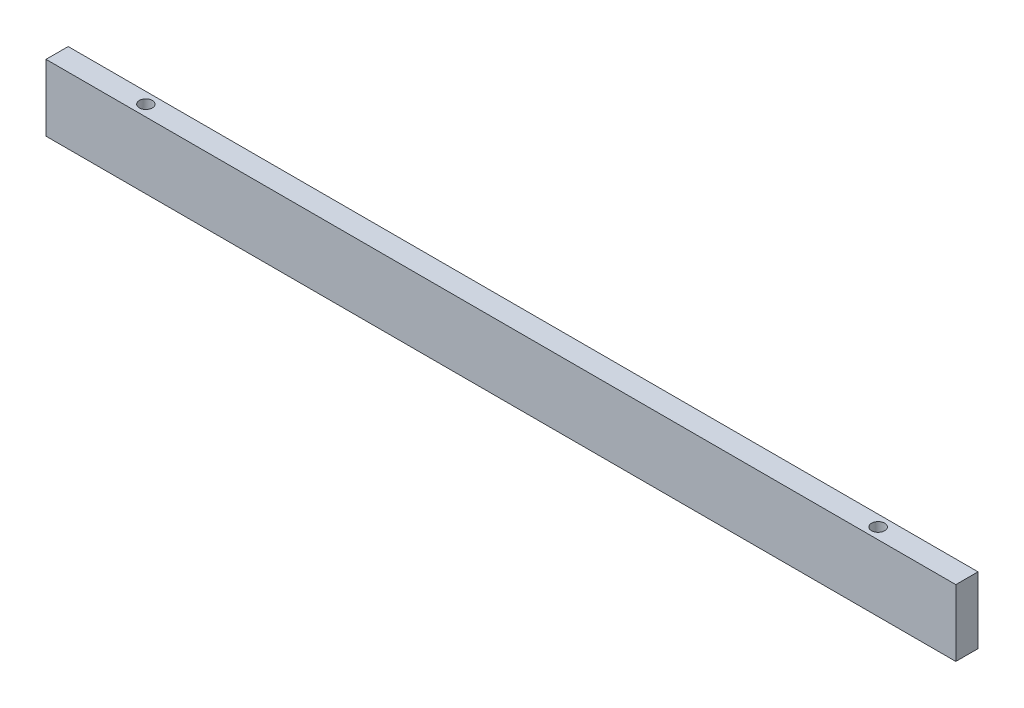
SolidWorks part; units mm, degrees
ref_plane "Front Plane" through (0, 0, 0) normal (0, 0, 1) x (1, 0, 0)
ref_plane "Top Plane" through (0, 0, 0) normal (0, 1, 0) x (1, 0, 0)
ref_plane "Right Plane" through (0, 0, 0) normal (1, 0, 0) x (0, 0, -1)
sketch "Sketch1" plane through (0, 0, 0) normal (0, 0, 1) x (1, 0, 0)
  line L0 (0, 0) -> (260.35, 0)
  line L1 (260.35, 0) -> (260.35, -19.05)
  line L2 (260.35, -19.05) -> (0, -19.05)
  line L3 (0, -19.05) -> (0, 0)
extrude "Boss-Extrude1" add sketch "Sketch1" along normal blind 6.35
sketch "Sketch2" plane through (0, 0, 0) normal (0, 1, 0) x (1, 0, 0)
  line L0 (260.35, -6.35) -> (260.35, 0) construction
  line L1 (0, -6.35) -> (0, 0) construction
  circle A0 centre (234.95, -3.175) radius 1.8836
  circle A1 centre (25.4, -3.175) radius 1.8665
  point P4 (260.35, -3.175)
  dimension "D1" = 25.4
  dimension "D2" = 25.4
extrude "Cut-Extrude1" cut sketch "Sketch2" against normal blind 6.35
sketch "Sketch3" plane through (0, -19.05, 0) normal (0, -1, 0) x (-1, 0, 0)
  line L0 (-260.35, -6.35) -> (-260.35, 0) construction
  line L1 (0, -6.35) -> (0, 0) construction
  circle A0 centre (-222.25, -3.175) radius 1.85
  circle A1 centre (-38.1, -3.175) radius 1.85
  dimension "D1" = 38.1
  dimension "D2" = 38.1
extrude "Cut-Extrude2" cut sketch "Sketch3" against normal blind 6.35
